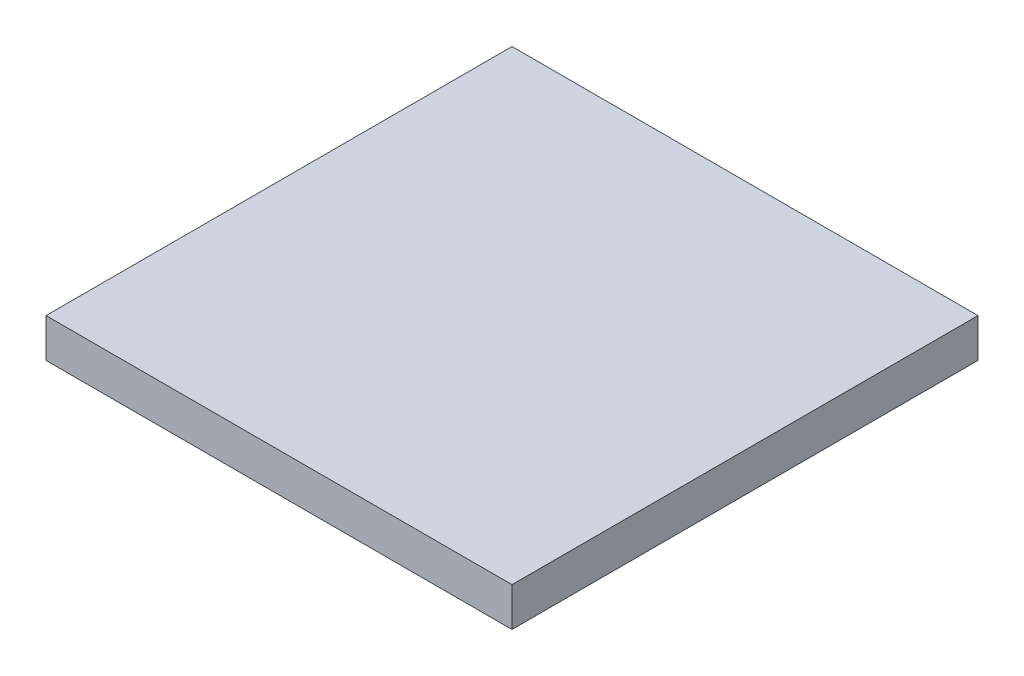
SolidWorks part; units mm, degrees
ref_plane "Piano frontale" through (0, 0, 0) normal (0, 0, 1) x (1, 0, 0)
ref_plane "Piano superiore" through (0, 0, 0) normal (0, 1, 0) x (1, 0, 0)
ref_plane "Piano destro" through (0, 0, 0) normal (1, 0, 0) x (0, 0, -1)
sketch "Schizzo2" plane through (0, 0, 0) normal (0, 1, 0) x (1, 0, 0)
  line L0 (-2.6639, -29.6899) -> (117.3361, -29.6899)
  line L1 (117.3361, -29.6899) -> (117.3361, -149.6899)
  line L2 (117.3361, -149.6899) -> (-2.6639, -149.6899)
  line L3 (-2.6639, -149.6899) -> (-2.6639, -29.6899)
  dimension "D1" = 120
  dimension "D2" = 120
extrude "Estrusione-Estrusione2" add sketch "Schizzo2" along normal blind 10
sketch "Schizzo3" plane through (0, 10, 0) normal (0, 1, 0) x (1, 0, 0)
  line L0 (117.3361, -38.6439) -> (-2.6639, -38.6439) construction
  line L1 (117.3361, -149.6899) -> (117.3361, -29.6899) construction
  line L2 (-2.6639, -29.6899) -> (-2.6639, -149.6899) construction
  line L3 (-2.6639, -38.6439) -> (-2.6639, -138.6439) construction
  line L4 (-2.6639, -138.6439) -> (117.3361, -138.6439) construction
  line L5 (87.2887, -249.679) -> (983.2887, -249.679) construction
  line L6 (-172.811, -0.173) -> (723.189, -0.173) construction
  line L7 (-165.1322, 59.6149) -> (730.8678, 59.6149) construction
  line L8 (224, 365.5) -> (1120, 365.5) construction
  dimension "D1" = 100
sketch "Schizzo4" plane through (0, 10, 0) normal (0, 1, 0) x (1, 0, 0)
  line L0 (224, 365.5) -> (1120, 365.5) construction
